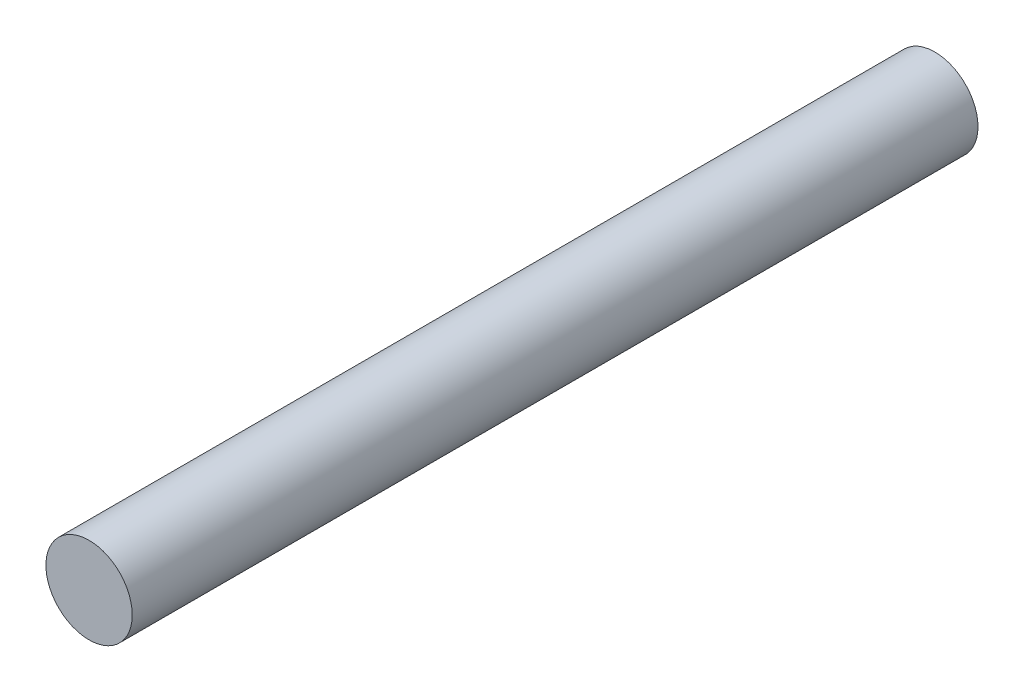
SolidWorks part; units mm, degrees
material "1060 Alloy"
ref_plane "Front Plane" through (0, 0, 0) normal (0, 0, 1) x (1, 0, 0)
ref_plane "Top Plane" through (0, 0, 0) normal (0, 1, 0) x (1, 0, 0)
ref_plane "Right Plane" through (0, 0, 0) normal (1, 0, 0) x (0, 0, -1)
sketch "Sketch1" plane through (0, 0, 0) normal (0, 0, 1) x (1, 0, 0)
  circle A0 centre (0, 0) radius 2.5
extrude "Boss-Extrude1" add sketch "Sketch1" along normal blind 49
ref_plane "Plane1" through (0, 0, 33.5) normal (0, 0, 1) x (1, 0, 0)
